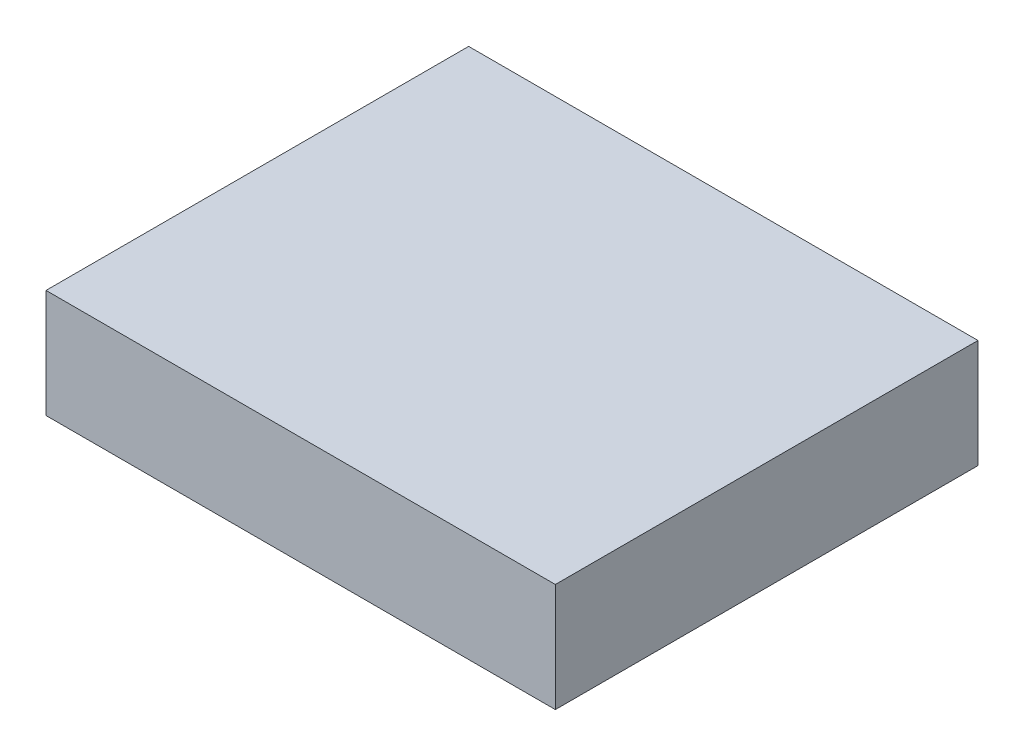
SolidWorks part; units mm, degrees
material "1060 Alloy"
ref_plane "Front Plane" through (0, 0, 0) normal (0, 0, 1) x (1, 0, 0)
ref_plane "Top Plane" through (0, 0, 0) normal (0, 1, 0) x (1, 0, 0)
ref_plane "Right Plane" through (0, 0, 0) normal (1, 0, 0) x (0, 0, -1)
sketch "Sketch1" plane through (0, 0, 0) normal (0, 1, 0) x (1, 0, 0)
  line L1 (0, 0) -> (-47, 0)
  line L2 (0, 0) -> (0, 39)
  line L3 (0, 39) -> (-47, 39)
  line L4 (-47, 0) -> (-47, 39)
  dimension "D1" = 39
  dimension "D2" = 47
extrude "Boss-Extrude1" add sketch "Sketch1" along normal blind 10
